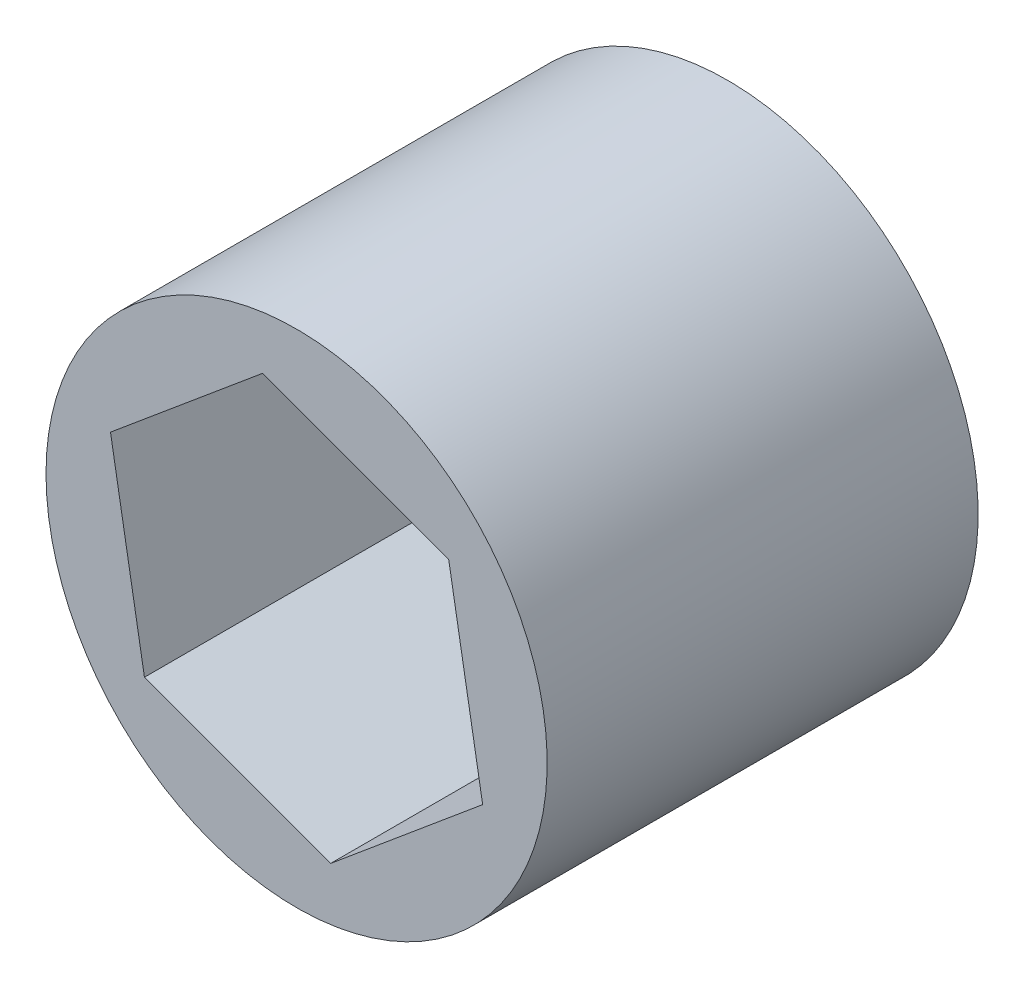
SolidWorks part; units mm, degrees
ref_plane "Front Plane" through (0, 0, 0) normal (0, 0, 1) x (1, 0, 0)
ref_plane "Top Plane" through (0, 0, 0) normal (0, 1, 0) x (1, 0, 0)
ref_plane "Right Plane" through (0, 0, 0) normal (1, 0, 0) x (0, 0, -1)
sketch "Sketch1" plane through (0, 0, 0) normal (0, 0, 1) x (1, 0, 0)
  line L1 (-7.4262, 2.723) -> (-6.0713, -5.0698)
  line L2 (-6.0713, -5.0698) -> (1.355, -7.7928)
  line L3 (1.355, -7.7928) -> (7.4262, -2.723)
  line L4 (7.4262, -2.723) -> (6.0713, 5.0698)
  line L5 (6.0713, 5.0698) -> (-1.355, 7.7928)
  line L6 (-1.355, 7.7928) -> (-7.4262, 2.723)
  circle A0 centre (0, 0) radius 10
  circle A1 centre (0, 0) radius 6.85 construction
  dimension "D1" = 13.7
  dimension "D2" = 20
extrude "Boss-Extrude1" add sketch "Sketch1" along normal blind 17.2
